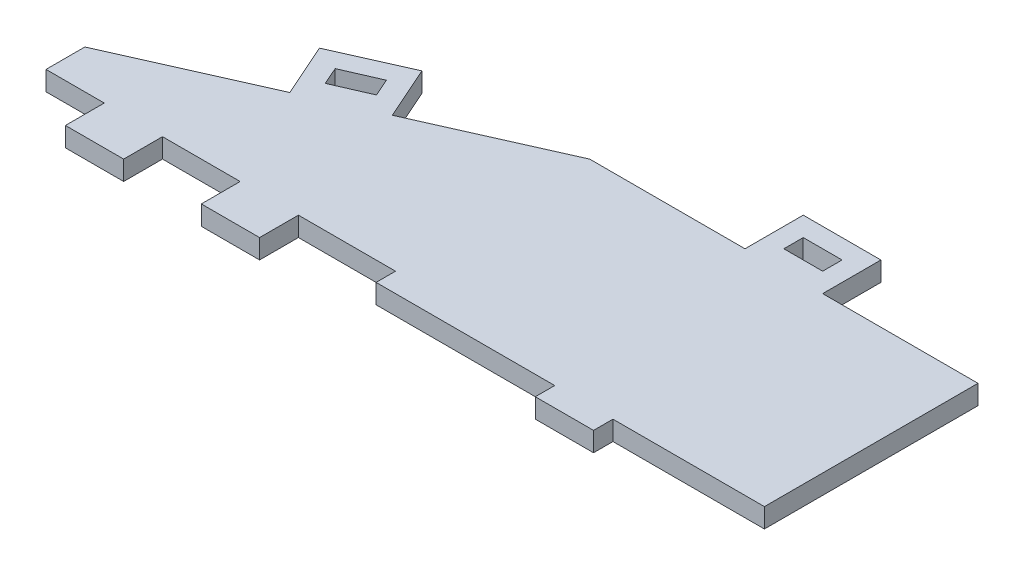
SolidWorks part; units mm, degrees
ref_plane "Спереди" through (0, 0, 0) normal (0, 0, 1) x (1, 0, 0)
ref_plane "Сверху" through (0, 0, 0) normal (0, 1, 0) x (1, 0, 0)
ref_plane "Справа" through (0, 0, 0) normal (1, 0, 0) x (0, 0, -1)
sketch "Sketch1" plane through (0, 0, 0) normal (0, 1, 0) x (1, 0, 0)
  line L0 (0, 0) -> (15, 0)
  line L1 (15, 0) -> (15, -10)
  line L2 (15, -10) -> (30, -10)
  line L3 (30, -10) -> (30, 0)
  line L4 (30, 0) -> (50, 0)
  line L5 (50, 0) -> (50, -10)
  line L6 (50, -10) -> (65, -10)
  line L7 (65, -10) -> (65, 0)
  line L8 (65, 0) -> (90, 0)
  line L9 (0, 0) -> (0, 10)
  line L10 (90, 0) -> (90, -5)
  line L11 (0, 10) -> (36.5525, 26.2455)
  line L12 (90, 0) -> (90, 50) construction
  line L13 (36.5525, 26.2455) -> (30.4604, 39.9527)
  line L14 (30.4604, 39.9527) -> (48.7366, 48.0755)
  line L15 (48.7366, 48.0755) -> (54.8287, 34.3683)
  line L16 (39.0615, 32.8324) -> (37.0601, 37.4143)
  line L17 (37.0601, 37.4143) -> (46.2241, 41.417)
  line L18 (46.2241, 41.417) -> (48.2548, 36.848)
  line L20 (54.8287, 34.3683) -> (90, 50)
  line L21 (90, 50) -> (130, 50)
  line L22 (190, 50) -> (190, -5)
  line L23 (190, -5) -> (151, -5)
  line L26 (130, 50) -> (130, 65)
  line L27 (130, 65) -> (150, 65)
  line L28 (150, 50) -> (150, 65)
  line L30 (135, 55) -> (135, 60)
  line L31 (135, 60) -> (145, 60)
  line L32 (145, 55) -> (145, 60)
  line L33 (150, 50) -> (190, 50)
  line L34 (136, -5) -> (90, -5)
  line L36 (136, -5) -> (136, -10)
  line L37 (136, -10) -> (151, -10)
  line L38 (151, -5) -> (151, -10)
  line L39 (39.0615, 32.8324) -> (48.2548, 36.848)
  line L40 (135, 55) -> (145, 55)
  point P28 (130, 57.5)
  dimension "D1" = 15
  dimension "D2" = 10
  dimension "D3" = 10
  dimension "D4" = 20
  dimension "D5" = 15
  dimension "D6" = 15
  dimension "D7" = 10
  dimension "D8" = 25
  dimension "D9" = 10
  dimension "D10" = 50
  dimension "D11" = 20
  dimension "D12" = 15
  dimension "D13" = 10
  dimension "D14" = 5
  dimension "D15" = 40
  dimension "D16" = 5
  dimension "D17" = 5.0002
  dimension "D18" = 100
  dimension "D19" = 40
  dimension "D20" = 20
  dimension "D21" = 5
  dimension "D22" = 5
  dimension "D23" = 10
  dimension "D24" = 15
  dimension "D25" = 15
  dimension "D26" = 55
  dimension "D27" = 5
  dimension "D28" = 5
  dimension "D29" = 15
  dimension "D30" = 71
  dimension "D31" = 5
  dimension "D32" = 5
extrude "Boss-Extrude1" add sketch "Sketch1" along normal blind 5
